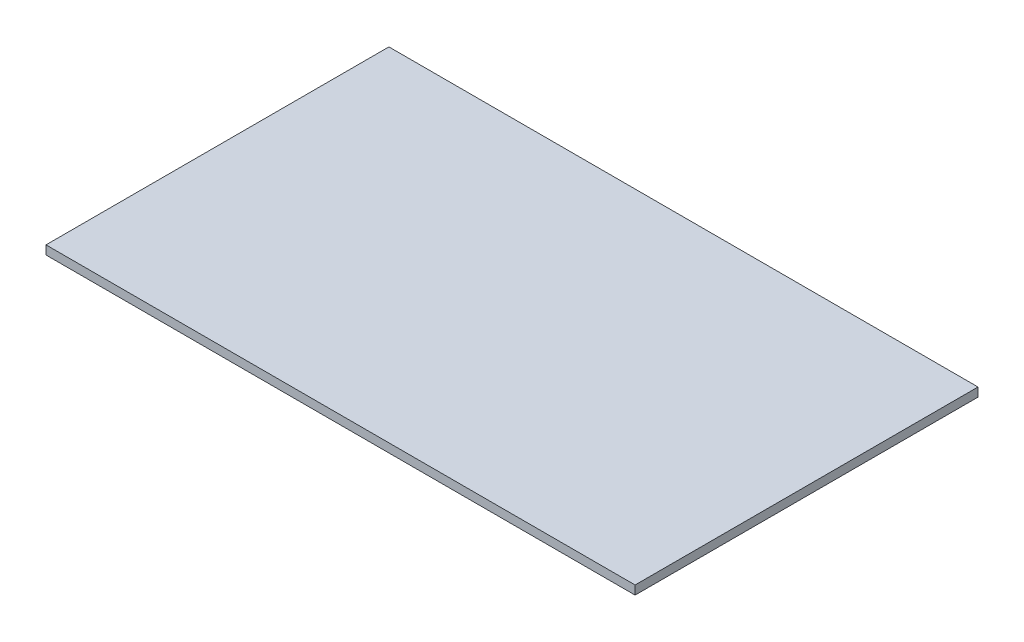
SolidWorks part; units mm, degrees
ref_plane "前视基准面" through (0, 0, 0) normal (0, 0, 1) x (1, 0, 0)
ref_plane "上视基准面" through (0, 0, 0) normal (0, 1, 0) x (1, 0, 0)
ref_plane "右视基准面" through (0, 0, 0) normal (1, 0, 0) x (0, 0, -1)
sketch "草图1" plane through (0, 0, 0) normal (0, 1, 0) x (1, 0, 0)
  line L1 (-33.5, 19.5) -> (33.5, 19.5)
  line L2 (-33.5, 19.5) -> (-33.5, -19.5)
  line L3 (-33.5, -19.5) -> (33.5, -19.5)
  line L4 (33.5, 19.5) -> (33.5, -19.5)
  line L5 (-33.5, 19.5) -> (33.5, -19.5) construction
  line L6 (-33.5, -19.5) -> (33.5, 19.5) construction
  point P0 (0, 0)
  dimension "D1" = 39
  dimension "D2" = 67
extrude "凸台-拉伸1" add sketch "草图1" along normal blind 1
